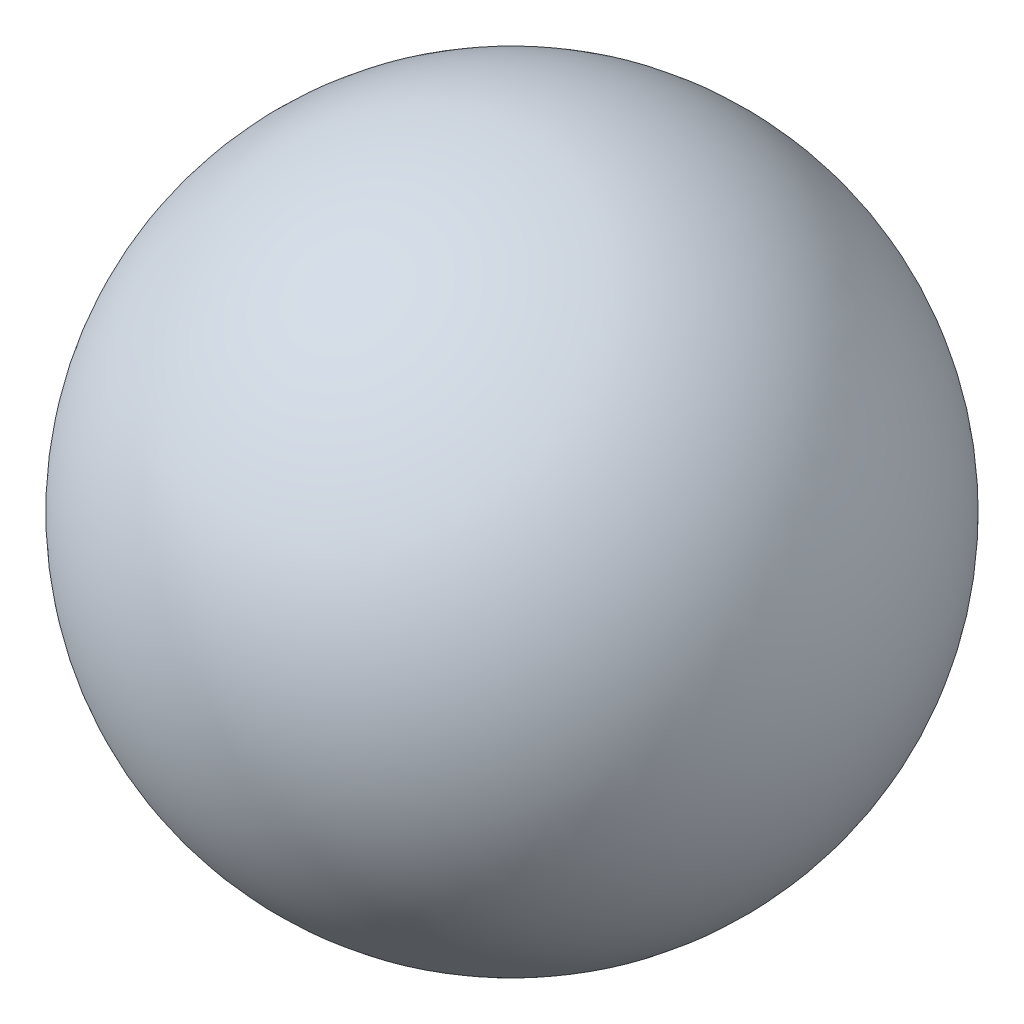
SolidWorks part; units mm, degrees
ref_plane "Front Plane" through (0, 0, 0) normal (0, 0, 1) x (1, 0, 0)
ref_plane "Top Plane" through (0, 0, 0) normal (0, 1, 0) x (1, 0, 0)
ref_plane "Right Plane" through (0, 0, 0) normal (1, 0, 0) x (0, 0, -1)
sketch "Sketch1" plane through (0, 0, 0) normal (0, 0, 1) x (1, 0, 0)
  line L0 (0, 0) -> (0, 50)
  arc A0 (0, 50) -> (0, 0) centre (0, 25) ccw
  dimension "D1" = 25
revolve "Revolve1" add sketch "Sketch1" angle 360 about L0
